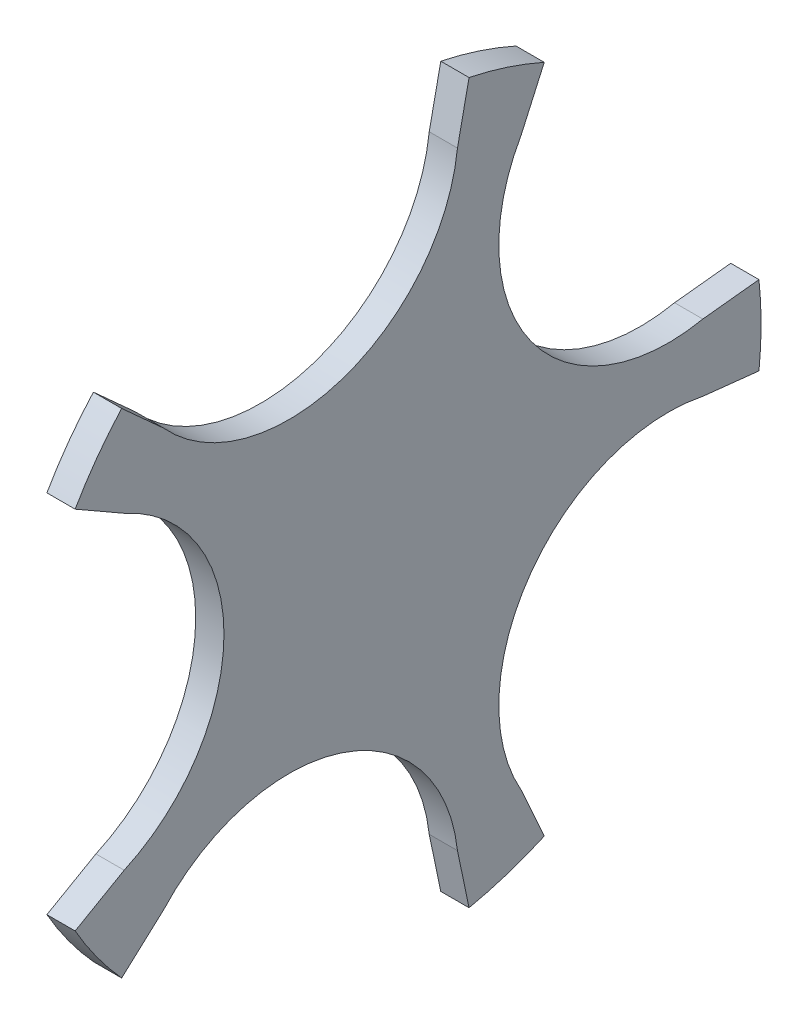
SolidWorks part; units mm, degrees
ref_plane "Piano frontale" through (0, 0, 0) normal (0, 0, 1) x (1, 0, 0)
ref_plane "Piano superiore" through (0, 0, 0) normal (0, 1, 0) x (1, 0, 0)
ref_plane "Piano destro" through (0, 0, 0) normal (1, 0, 0) x (0, 0, -1)
ref_plane "Piano1" through (6.1538, 0, 0) normal (1, 0, 0) x (0, 0, -1)
sketch "Schizzo1" plane through (6.1538, 0, 0) normal (1, 0, 0) x (0, 0, -1)
  line L0 (-4.8167, -4.3646) -> (-4.0758, -3.6932)
  line L1 (1.1266, -5.3836) -> (1.3313, -6.3622)
  line L2 (2.6625, -5.9297) -> (2.253, -5.0176)
  line L3 (5.4682, -0.5922) -> (6.4622, -0.6999)
  line L4 (6.4622, 0.6999) -> (5.4682, 0.5922)
  line L5 (2.253, 5.0176) -> (2.6625, 5.9297)
  line L6 (1.3313, 6.3622) -> (1.1266, 5.3836)
  line L7 (-4.0758, 3.6932) -> (-4.8167, 4.3646)
  line L8 (-5.6394, 3.2322) -> (-4.772, 2.735)
  line L9 (-4.772, -2.735) -> (-5.6394, -3.2322)
  arc A0 (-5.6394, -3.2322) -> (-4.8167, -4.3646) centre (0, 0) ccw
  arc A1 (-4.0758, -3.6932) -> (1.1266, -5.3836) centre (-1.856, -5.7121) cw
  arc A2 (1.3313, -6.3622) -> (2.6625, -5.9297) centre (0, 0) ccw
  arc A3 (2.253, -5.0176) -> (5.4682, -0.5922) centre (4.859, -3.5302) cw
  arc A4 (6.4622, -0.6999) -> (6.4622, 0.6999) centre (0, 0) ccw
  arc A5 (5.4682, 0.5922) -> (2.253, 5.0176) centre (4.859, 3.5302) cw
  arc A6 (2.6625, 5.9297) -> (1.3313, 6.3622) centre (0, 0) ccw
  arc A7 (1.1266, 5.3836) -> (-4.0758, 3.6932) centre (-1.856, 5.7121) cw
  arc A8 (-4.8167, 4.3646) -> (-5.6394, 3.2322) centre (0, 0) ccw
  arc A9 (-4.772, 2.735) -> (-4.772, -2.735) centre (-6.006, 0) cw
extrude "Estrusione-Estrusione1" add sketch "Schizzo1" against normal blind 0.5
